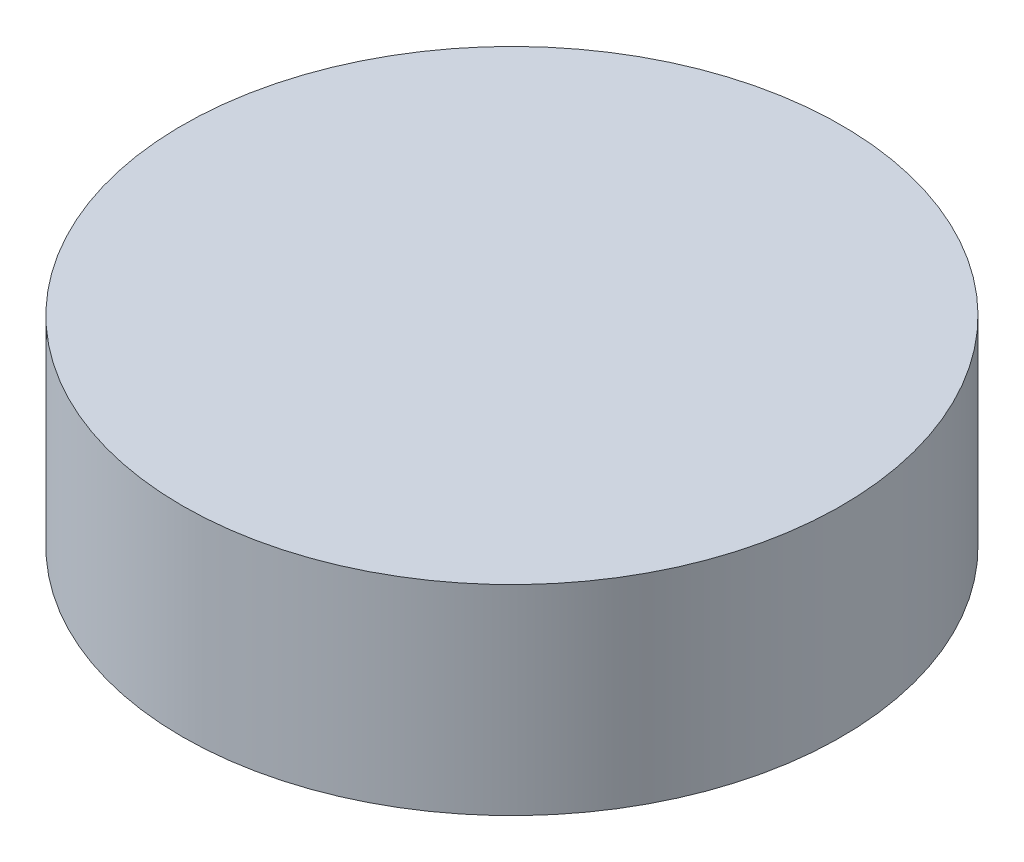
SolidWorks part; units mm, degrees
ref_plane "Front" through (0, 0, 0) normal (0, 0, 1) x (1, 0, 0)
ref_plane "Top" through (0, 0, 0) normal (0, 1, 0) x (1, 0, 0)
ref_plane "Right" through (0, 0, 0) normal (1, 0, 0) x (0, 0, -1)
sketch "Sketch1" plane through (0, 0, 0) normal (0, 1, 0) x (1, 0, 0)
  circle A0 centre (-28.1409, -14.8885) radius 28
extrude "Boss-Extrude1" add sketch "Sketch1" along normal blind 17
